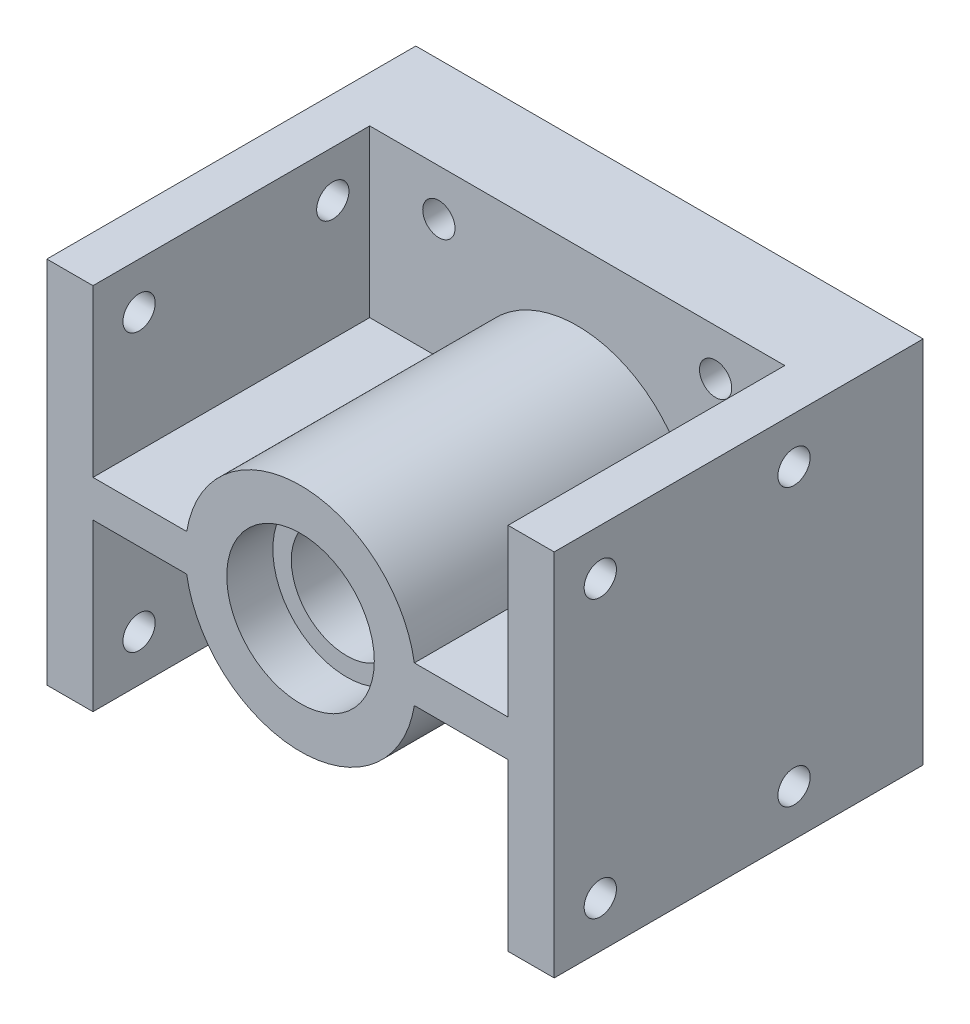
SolidWorks part; units mm, degrees
ref_plane "Front Plane" through (0, 0, 0) normal (0, 0, 1) x (1, 0, 0)
ref_plane "Top Plane" through (0, 0, 0) normal (0, 1, 0) x (1, 0, 0)
ref_plane "Right Plane" through (0, 0, 0) normal (1, 0, 0) x (0, 0, -1)
sketch "Sketch1" plane through (0, 0, 0) normal (0, 0, 1) x (1, 0, 0)
  line L1 (-22.5, 20) -> (22.5, 20)
  line L2 (-22.5, 20) -> (-22.5, -20)
  line L3 (-22.5, -20) -> (22.5, -20)
  line L4 (22.5, 20) -> (22.5, -20)
  line L5 (-22.5, 20) -> (22.5, -20) construction
  line L6 (-22.5, -20) -> (22.5, 20) construction
  point P0 (0, 0)
  dimension "D1" = 45
  dimension "D2" = 40
extrude "Boss-Extrude1" add sketch "Sketch1" along normal blind 10
sketch "Sketch2" plane through (0, 0, 0) normal (0, 0, 1) x (1, 0, 0)
  line L0 (0, 4.5451) -> (0, 0) construction
  line L1 (-27.5, 20) -> (-22.5, 20)
  line L2 (-27.5, 20) -> (-27.5, -20)
  line L3 (-27.5, -20) -> (-22.5, -20)
  line L4 (-22.5, 20) -> (-22.5, -20)
  line L5 (-27.5, 20) -> (-22.5, -20) construction
  line L6 (-27.5, -20) -> (-22.5, 20) construction
  line L7 (27.5, -20) -> (22.5, 20) construction
  line L8 (27.5, 20) -> (22.5, -20) construction
  line L9 (22.5, 20) -> (22.5, -20)
  line L10 (27.5, -20) -> (22.5, -20)
  line L11 (27.5, 20) -> (27.5, -20)
  line L12 (27.5, 20) -> (22.5, 20)
  point P0 (-25, 0)
  point P13 (25, 0)
  dimension "D1" = 5
  dimension "D2" = 5
  dimension "D3" = 5
extrude "Boss-Extrude2" add sketch "Sketch2" along normal blind 40
sketch "Sketch3" plane through (0, 0, 10) normal (0, 0, 1) x (1, 0, 0)
  circle A0 centre (0, 0) radius 12.5
  dimension "D1" = 25
extrude "Boss-Extrude3" add sketch "Sketch3" along normal blind 30
sketch "Sketch4" plane through (0, 0, 0) normal (0, 0, -1) x (-1, 0, 0)
  circle A0 centre (0, 0) radius 6
  dimension "D1" = 12
extrude "Cut-Extrude1" cut sketch "Sketch4" against normal through all
sketch "Sketch5" plane through (0, 0, 40) normal (0, 0, 1) x (1, 0, 0)
  circle A0 centre (0, 0) radius 8
  dimension "D1" = 16
extrude "Cut-Extrude2" cut sketch "Sketch5" against normal blind 5
sketch "Sketch6" plane through (0, 0, 0) normal (0, 0, -1) x (-1, 0, 0)
  line L0 (3.1808, 0) -> (0, 0) construction
  line L1 (0, 0) -> (0, 3.7375) construction
  circle A0 centre (-15, 15) radius 1.75
  circle A1 centre (15, 15) radius 1.75
  circle A2 centre (15, -15) radius 1.75
  circle A3 centre (-15, -15) radius 1.75
  dimension "D1" = 3.5
  dimension "D2" = 15
  dimension "D3" = 15
extrude "Cut-Extrude3" cut sketch "Sketch6" against normal through all
sketch "Sketch7" plane through (0, 0, 10) normal (0, 0, 1) x (1, 0, 0)
  line L0 (-22.5, -20) -> (-22.5, 20) construction
  line L1 (-22.5, 2) -> (-11.5, 2)
  line L2 (-22.5, 2) -> (-22.5, -2)
  line L3 (-22.5, -2) -> (-11.5, -2)
  line L4 (-11.5, 2) -> (-11.5, -2)
  line L5 (0, -1.3447) -> (0, 0) construction
  line L6 (11.5, 2) -> (11.5, -2)
  line L7 (22.5, -2) -> (11.5, -2)
  line L8 (22.5, 2) -> (22.5, -2)
  line L9 (22.5, 2) -> (11.5, 2)
  point P6 (-11.5, 0)
  dimension "D1" = 4
  dimension "D2" = 11
extrude "Boss-Extrude4" add sketch "Sketch7" along normal blind 30
sketch "Sketch8" plane through (-27.5, 0, 0) normal (-1, 0, 0) x (0, 0, 1)
  line L0 (40, 20) -> (0, 20) construction
  line L1 (40, 20) -> (40, -20) construction
  line L2 (10.1617, 0) -> (21.551, 0) construction
  line L3 (0, 20) -> (0, -20) construction
  circle A0 centre (35, 15) radius 1.75
  circle A1 centre (35, -15) radius 1.75
  circle A2 centre (14, 15) radius 1.75
  circle A3 centre (14, -15) radius 1.75
  dimension "D1" = 3.5
  dimension "D4" = 3.5
  dimension "D2" = 5
  dimension "D3" = 5
  dimension "D5" = 14
extrude "Cut-Extrude4" cut sketch "Sketch8" against normal through all
